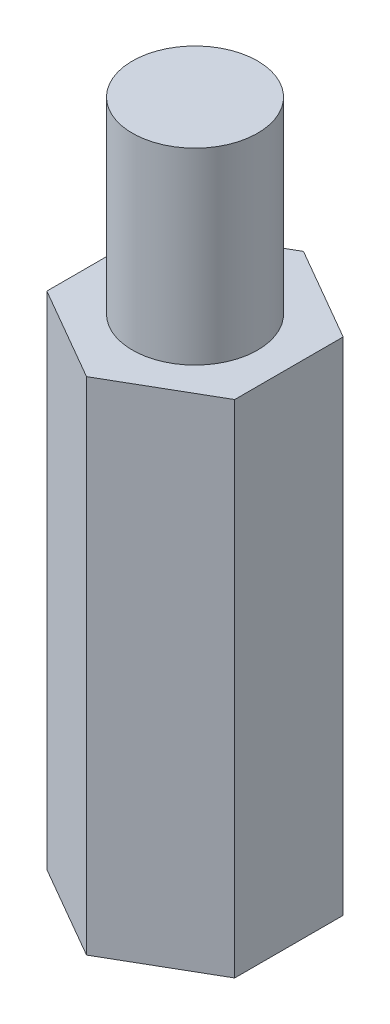
SolidWorks part; units mm, degrees
material "AISI 304"
ref_plane "Front Plane" through (0, 0, 0) normal (0, 0, 1) x (1, 0, 0)
ref_plane "Top Plane" through (0, 0, 0) normal (0, 1, 0) x (1, 0, 0)
ref_plane "Right Plane" through (0, 0, 0) normal (1, 0, 0) x (0, 0, -1)
sketch "Sketch1" plane through (0, 0, 0) normal (0, 1, 0) x (1, 0, 0)
  line L1 (0, 5.4993) -> (-4.7625, 2.7496)
  line L2 (-4.7625, 2.7496) -> (-4.7625, -2.7496)
  line L3 (-4.7625, -2.7496) -> (0, -5.4993)
  line L4 (0, -5.4993) -> (4.7625, -2.7496)
  line L5 (4.7625, -2.7496) -> (4.7625, 2.7496)
  line L6 (4.7625, 2.7496) -> (0, 5.4993)
  circle A1 centre (0, 0) radius 4.7625 construction
  dimension "D2" = 9.525
extrude "Boss-Extrude1" add sketch "Sketch1" along normal blind 25.4
sketch "Sketch2" plane through (0, 0, 0) normal (0, -1, 0) x (1, 0, 0)
  circle A0 centre (0, 0) radius 3.175
  dimension "D1" = 6.35
extrude "Cut-Extrude1" cut sketch "Sketch2" against normal blind 12.7
sketch "Sketch3" plane through (0, 25.4, 0) normal (0, 1, 0) x (1, 0, 0)
  circle A0 centre (0, 0) radius 3.175
  dimension "D1" = 6.35
extrude "Boss-Extrude2" add sketch "Sketch3" along normal blind 9.525
